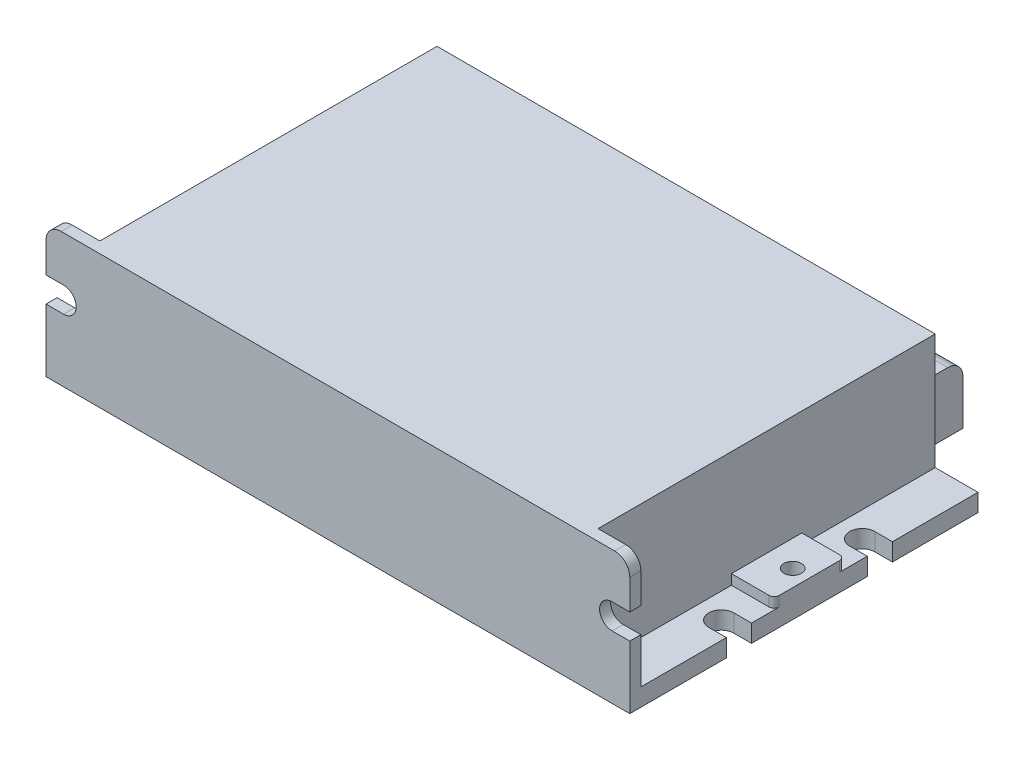
SolidWorks part; units mm, degrees
ref_plane "Front Plane" through (0, 0, 0) normal (0, 0, 1) x (1, 0, 0)
ref_plane "Top Plane" through (0, 0, 0) normal (0, 1, 0) x (1, 0, 0)
ref_plane "Right Plane" through (0, 0, 0) normal (1, 0, 0) x (0, 0, -1)
sketch "Sketch1" plane through (0, 0, 0) normal (0, 1, 0) x (1, 0, 0)
  line L1 (-49.5, -33.5) -> (49.5, -33.5)
  line L2 (-49.5, -33.5) -> (-49.5, 33.5)
  line L3 (-49.5, 33.5) -> (49.5, 33.5)
  line L4 (49.5, -33.5) -> (49.5, 33.5)
  line L5 (-49.5, -33.5) -> (49.5, 33.5) construction
  line L6 (-49.5, 33.5) -> (49.5, -33.5) construction
  point P0 (0, 0)
  dimension "D1" = 99
  dimension "D2" = 67
extrude "Boss-Extrude1" add sketch "Sketch1" along normal blind 23
sketch "Sketch2" plane through (0, 0, 0) normal (0, -1, 0) x (1, 0, 0)
  line L0 (49.5, -33.5) -> (-49.5, -33.5) construction
  line L1 (-58, -33.5) -> (58, -33.5)
  line L2 (-58, -33.5) -> (-58, 35.7)
  line L3 (-58, 35.7) -> (58, 35.7)
  line L4 (58, -33.5) -> (58, 35.7)
  line L5 (-58, -33.5) -> (58, 35.7) construction
  line L6 (-58, 35.7) -> (58, -33.5) construction
  point P0 (0, 1.1)
  dimension "D1" = 116
  dimension "D2" = 69.2
  dimension "D3" = 0
extrude "Boss-Extrude2" add sketch "Sketch2" along normal blind 3.5
sketch "Sketch3" plane through (0, 0, 0) normal (0, 1, 0) x (1, 0, 0)
  line L0 (58, 33.5) -> (58, -35.7) construction
  line L1 (-58, -35.7) -> (58, -35.7)
  line L2 (-58, -35.7) -> (-58, -33.5)
  line L3 (-58, -33.5) -> (58, -33.5)
  line L4 (58, -35.7) -> (58, -33.5)
extrude "Boss-Extrude3" add sketch "Sketch3" along normal up to surface (23 mm away) up to face at (0, 23, 0)
sketch "Sketch4" plane through (0, 0, -33.5) normal (0, 0, -1) x (-1, 0, 0)
  line L1 (-45.5, 11.9694) -> (45.5, 11.9694)
  line L2 (-45.5, 11.9694) -> (-45.5, 0)
  line L3 (-45.5, 0) -> (45.5, 0)
  line L4 (45.5, 11.9694) -> (45.5, 0)
  line L5 (-45.5, 11.9694) -> (45.5, 0) construction
  line L6 (-45.5, 0) -> (45.5, 11.9694) construction
  line L7 (49.5, 0) -> (58, 0) construction
  line L8 (-49.5, 23) -> (-49.5, 0) construction
  line L9 (49.5, 23) -> (49.5, 0) construction
  point P0 (0, 5.9847)
  dimension "D1" = 4
  dimension "D2" = 4
extrude "Boss-Extrude4" add sketch "Sketch4" along normal blind 9.5
fillet "Fillet1" radius 3 1 edges at (0, 11.9694, -43)
fillet "Fillet2" radius 3 2 edges at (-58, 23, 34.6) (58, 23, 34.6)
sketch "Sketch5" plane through (0, 0, 35.7) normal (0, 0, 1) x (1, 0, 0)
  line L0 (58, -3.5) -> (-58, -3.5) construction
  line L1 (-58, -3.5) -> (-58, 20) construction
  line L2 (0, 0) -> (0, 57.1502) construction
  line L3 (-54.5, 14) -> (-58, 14)
  line L4 (-58, 14) -> (-58, 9)
  line L5 (-58, 9) -> (-54.5, 9)
  line L6 (58, 9) -> (54.5, 9)
  line L7 (58, 14) -> (58, 9)
  line L8 (54.5, 14) -> (58, 14)
  arc A0 (-54.5, 9) -> (-54.5, 14) centre (-54.5, 11.5) ccw
  arc A2 (54.5, 9) -> (54.5, 14) centre (54.5, 11.5) cw
  dimension "D1" = 5
  dimension "D2" = 15
  dimension "D3" = 3.5
extrude "Cut-Extrude1" cut sketch "Sketch5" against normal blind 9.5
sketch "Sketch6" plane through (0, 0, 0) normal (0, 1, 0) x (1, 0, 0)
  line L0 (49.5, 33.5) -> (58, 33.5) construction
  line L1 (58, 33.5) -> (58, -33.5) construction
  line L2 (0, 0) -> (0, -59.9209) construction
  line L3 (54.5, 16.5) -> (58, 16.5)
  line L4 (58, 16.5) -> (58, 11.5)
  line L5 (58, 11.5) -> (54.5, 11.5)
  line L6 (54.5, -11.5) -> (58, -11.5)
  line L7 (58, -11.5) -> (58, -16.5)
  line L8 (58, -16.5) -> (54.5, -16.5)
  line L9 (-58, -16.5) -> (-54.5, -16.5)
  line L10 (-58, -11.5) -> (-58, -16.5)
  line L11 (-54.5, -11.5) -> (-58, -11.5)
  line L12 (-58, 11.5) -> (-54.5, 11.5)
  line L13 (-58, 16.5) -> (-58, 11.5)
  line L14 (-54.5, 16.5) -> (-58, 16.5)
  arc A0 (54.5, 16.5) -> (54.5, 11.5) centre (54.5, 14) ccw
  arc A1 (54.5, -11.5) -> (54.5, -16.5) centre (54.5, -14) ccw
  arc A2 (-54.5, -11.5) -> (-54.5, -16.5) centre (-54.5, -14) cw
  arc A3 (-54.5, 16.5) -> (-54.5, 11.5) centre (-54.5, 14) cw
  dimension "D1" = 5
  dimension "D3" = 5
  dimension "D2" = 19.5
  dimension "D4" = 28
  dimension "D5" = 3.5
extrude "Cut-Extrude2" cut sketch "Sketch6" against normal blind 9.5
sketch "Sketch8" plane through (0, 0, 0) normal (0, 1, 0) x (1, 0, 0)
  line L0 (-49.5, 33.5) -> (-49.5, -33.5) construction
  line L1 (-57, -7) -> (-49.5, -7)
  line L2 (-58, -6) -> (-58, 6)
  line L3 (-57, 7) -> (-49.5, 7)
  line L4 (-49.5, -7) -> (-49.5, 7)
  line L5 (0, 0) -> (0, 33.5) construction
  line L6 (-45.5, 33.5) -> (45.5, 33.5) construction
  line L8 (49.5, -7) -> (49.5, 7)
  line L9 (57, 7) -> (49.5, 7)
  line L10 (58, -6) -> (58, 6)
  line L11 (57, -7) -> (49.5, -7)
  arc A0 (-57, -7) -> (-58, -6) centre (-57, -6) cw
  arc A1 (-58, 6) -> (-57, 7) centre (-57, 6) cw
  arc A2 (58, 6) -> (57, 7) centre (57, 6) ccw
  arc A3 (57, -7) -> (58, -6) centre (57, -6) ccw
  point P0 (-53.75, 0)
  point P24 (53.75, 0)
  dimension "D1" = 1
extrude "Boss-Extrude5" add sketch "Sketch8" along normal blind 2
sketch "Sketch9" plane through (0, 2, 0) normal (0, 1, 0) x (1, 0, 0)
  line L0 (0, 0) -> (0, 33.5) construction
  line L1 (-45.5, 33.5) -> (45.5, 33.5) construction
  circle A0 centre (-54.6785, 0) radius 1.728
  circle A1 centre (54.6785, 0) radius 1.728
extrude "Cut-Extrude3" cut sketch "Sketch9" against normal through all
